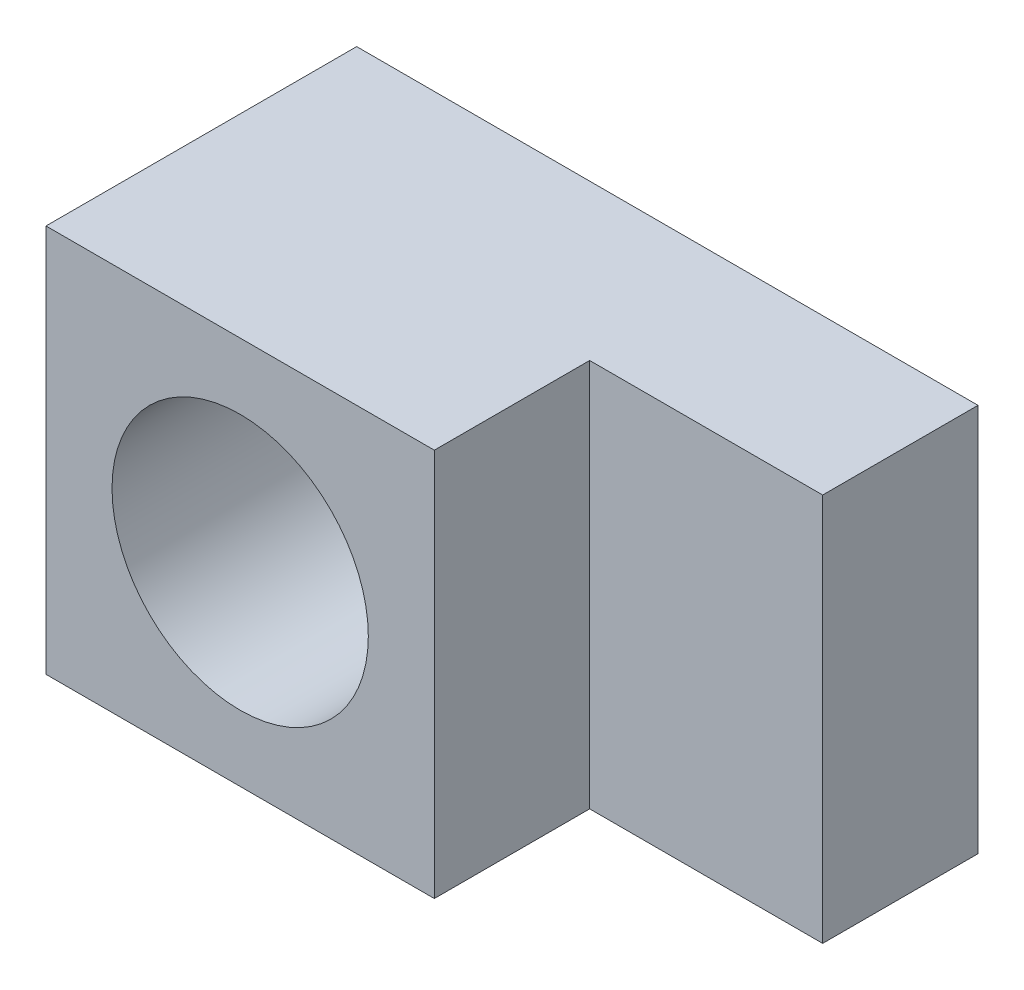
SolidWorks part; units mm, degrees
material "ABS"
ref_plane "Front" through (0, 0, 0) normal (0, 0, 1) x (1, 0, 0)
ref_plane "Top" through (0, 0, 0) normal (0, 1, 0) x (1, 0, 0)
ref_plane "Right" through (0, 0, 0) normal (1, 0, 0) x (0, 0, -1)
sketch "Эскиз1" plane through (0, 0, 0) normal (0, 0, 1) x (1, 0, 0)
  line L1 (-4, 2.5) -> (4, 2.5)
  line L2 (-4, 2.5) -> (-4, -2.5)
  line L3 (-4, -2.5) -> (4, -2.5)
  line L4 (4, 2.5) -> (4, -2.5)
  line L5 (-4, 2.5) -> (4, -2.5) construction
  line L6 (-4, -2.5) -> (4, 2.5) construction
  point P0 (0, 0)
  dimension "D1" = 8
  dimension "D2" = 5
extrude "Бобышка-Вытянуть1" add sketch "Эскиз1" along normal blind 4
sketch "Эскиз2" plane through (4, 0, 0) normal (1, 0, 0) x (0, 0, -1)
  line L0 (-4, -2.5) -> (0, -2.5) construction
  line L1 (-4, 2.5) -> (-2, 2.5)
  line L2 (-4, 2.5) -> (-4, -2.5)
  line L3 (-4, -2.5) -> (-2, -2.5)
  line L4 (-2, 2.5) -> (-2, -2.5)
extrude "Вырез-Вытянуть1" cut sketch "Эскиз2" against normal blind 3
sketch "Эскиз3" plane through (0, 0, 4) normal (0, 0, 1) x (1, 0, 0)
  line L0 (1, 2.5) -> (-4, 2.5) construction
  line L1 (-4, 2.5) -> (-4, -2.5) construction
  circle A0 centre (-1.5, 0) radius 1.65
  dimension "D1" = 2.5
  dimension "D2" = 2.5
extrude "Вырез-Вытянуть2" cut sketch "Эскиз3" against normal blind 5
